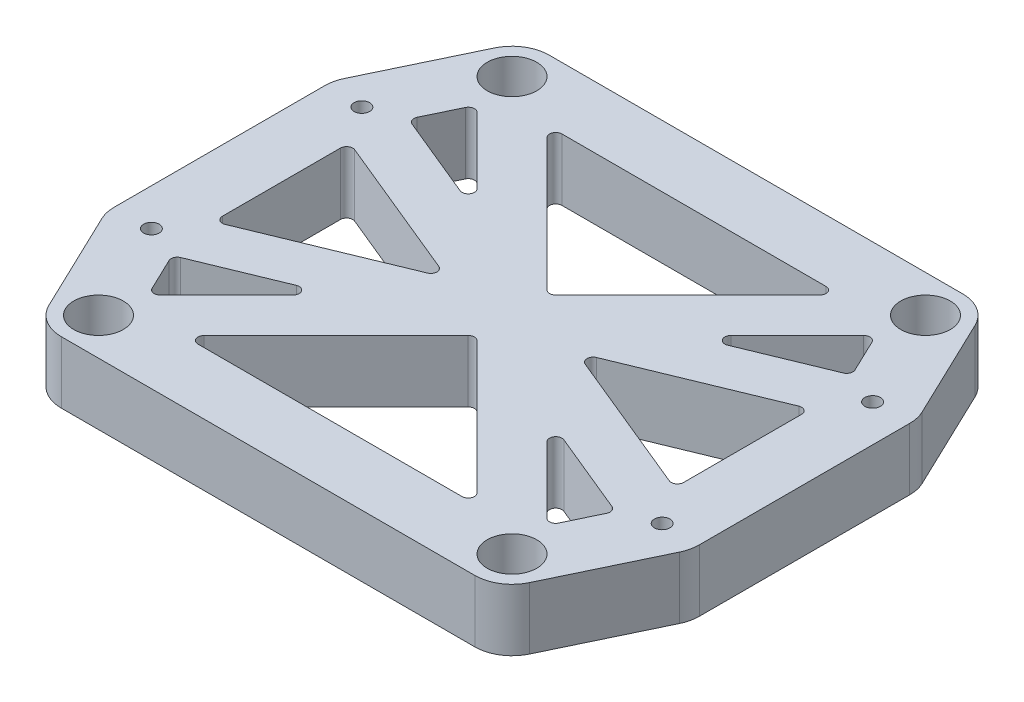
SolidWorks part; units mm, degrees
ref_plane "Front Plane" through (0, 0, 0) normal (0, 0, 1) x (1, 0, 0)
ref_plane "Top Plane" through (0, 0, 0) normal (0, 1, 0) x (1, 0, 0)
ref_plane "Right Plane" through (0, 0, 0) normal (1, 0, 0) x (0, 0, -1)
sketch "Sketch1" plane through (0, 0, 0) normal (0, 1, 0) x (1, 0, 0)
  line L1 (-52.3875, -21.59) -> (52.3875, -21.59) construction
  line L2 (-52.3875, -21.59) -> (-52.3875, 21.59) construction
  line L3 (-52.3875, 21.59) -> (52.3875, 21.59) construction
  line L4 (52.3875, -21.59) -> (52.3875, 21.59) construction
  line L5 (-52.3875, -21.59) -> (52.3875, 21.59) construction
  line L6 (-52.3875, 21.59) -> (52.3875, -21.59) construction
  line L7 (-42.418, -42.418) -> (42.418, -42.418) construction
  line L8 (-42.418, -42.418) -> (-42.418, 42.418) construction
  line L9 (-42.418, 42.418) -> (42.418, 42.418) construction
  line L10 (42.418, -42.418) -> (42.418, 42.418) construction
  line L11 (-42.418, -42.418) -> (42.418, 42.418) construction
  line L12 (-42.418, 42.418) -> (42.418, -42.418) construction
  line L13 (-65.0875, -55.118) -> (65.0875, -55.118)
  line L14 (-65.0875, -55.118) -> (-65.0875, 55.118)
  line L15 (-65.0875, 55.118) -> (65.0875, 55.118)
  line L16 (65.0875, -55.118) -> (65.0875, 55.118)
  line L17 (-65.0875, -55.118) -> (65.0875, 55.118) construction
  line L18 (-65.0875, 55.118) -> (65.0875, -55.118) construction
  circle A0 centre (-52.3875, 21.59) radius 1.5875
  circle A1 centre (52.3875, 21.59) radius 1.5875
  circle A2 centre (52.3875, -21.59) radius 1.5875
  circle A3 centre (-52.3875, -21.59) radius 1.5875
  circle A4 centre (-42.418, 42.418) radius 5.08
  circle A5 centre (42.418, 42.418) radius 5.08
  circle A6 centre (42.418, -42.418) radius 5.08
  circle A7 centre (-42.418, -42.418) radius 5.08
  point P0 (0, 0)
  point P10 (0, 0)
  point P19 (0, 0)
  dimension "D1" = 3.175
  dimension "D4" = 10.16
  dimension "D2" = 104.775
  dimension "D3" = 43.18
  dimension "D5" = 84.836
  dimension "D6" = 12.7
  dimension "D7" = 12.7
extrude "Boss-Extrude1" add sketch "Sketch1" along normal blind 12.7
sketch "Sketch2" plane through (0, 12.7, 0) normal (0, 1, 0) x (1, 0, 0)
  line L0 (-65.0875, 0) -> (65.0875, 0) construction
  line L1 (-65.0875, 55.118) -> (-65.0875, -55.118) construction
  line L2 (65.0875, -55.118) -> (65.0875, 55.118) construction
  line L3 (0, -55.118) -> (0, 55.118) construction
  line L4 (-65.0875, -55.118) -> (65.0875, -55.118) construction
  line L5 (65.0875, 55.118) -> (-65.0875, 55.118) construction
  line L6 (-42.418, 42.418) -> (-52.3875, 21.59) construction
  line L7 (-52.3875, 21.59) -> (-52.3875, -21.59) construction
  line L8 (-52.3875, -21.59) -> (-42.418, -42.418) construction
  line L9 (-42.418, -42.418) -> (42.418, -42.418) construction
  line L10 (42.418, -42.418) -> (52.3875, -21.59) construction
  line L11 (52.3875, -21.59) -> (52.3875, 21.59) construction
  line L12 (52.3875, 21.59) -> (42.418, 42.418) construction
  line L13 (42.418, 42.418) -> (-42.418, 42.418) construction
  line L14 (-42.418, 42.418) -> (0, 0) construction
  line L15 (0, 0) -> (-42.418, -42.418) construction
  line L16 (-52.3875, -21.59) -> (0, 0) construction
  line L17 (-52.3875, 21.59) -> (0, 0) construction
  line L18 (0, 0) -> (42.418, 42.418) construction
  line L19 (0, 0) -> (52.3875, 21.59) construction
  line L20 (0, 0) -> (52.3875, -21.59) construction
  line L21 (0, 0) -> (42.418, -42.418) construction
  line L22 (-27.0877, -37.338) -> (27.0877, -37.338)
  line L23 (0.898, -8.0822) -> (27.9858, -35.17)
  line L24 (-0.898, -8.0822) -> (-27.9858, -35.17)
  line L25 (-44.2456, -23.729) -> (-27.4425, -16.8041)
  line L26 (-26.0605, -18.8763) -> (-39.6659, -32.4817)
  line L27 (-44.9072, -25.4515) -> (-41.7095, -32.132)
  line L28 (-45.5536, -13.2791) -> (-16.1814, -1.1742)
  line L29 (-45.5536, 13.2791) -> (-16.1814, 1.1742)
  line L30 (-47.3075, 12.1049) -> (-47.3075, -12.1049)
  line L31 (-44.2456, 23.729) -> (-27.4425, 16.8041)
  line L32 (-39.6659, 32.4817) -> (-26.0605, 18.8763)
  line L33 (-41.7095, 32.132) -> (-44.9072, 25.4515)
  line L34 (0.898, 8.0822) -> (27.9858, 35.17)
  line L35 (27.0877, 37.338) -> (-27.0877, 37.338)
  line L36 (-27.9858, 35.17) -> (-0.898, 8.0822)
  line L37 (27.4425, 16.8041) -> (44.2456, 23.729)
  line L38 (44.9072, 25.4515) -> (41.7095, 32.132)
  line L39 (26.0605, 18.8763) -> (39.6659, 32.4817)
  line L40 (16.1814, 1.1742) -> (45.5536, 13.2791)
  line L41 (47.3075, -12.1049) -> (47.3075, 12.1049)
  line L42 (16.1814, -1.1742) -> (45.5536, -13.2791)
  line L43 (26.0605, -18.8763) -> (39.6659, -32.4817)
  line L44 (41.7095, -32.132) -> (44.9072, -25.4515)
  line L45 (27.4425, -16.8041) -> (44.2456, -23.729)
  line L46 (40.9348, -33.7506) -> (45.4868, -24.2406) construction
  line L47 (21.5669, -14.3827) -> (45.4868, -24.2406) construction
  line L48 (21.5669, -14.3827) -> (40.9348, -33.7506) construction
  line L49 (0, -7.1842) -> (30.1538, -37.338) construction
  line L50 (0, -7.1842) -> (-30.1538, -37.338) construction
  line L51 (-30.1538, -37.338) -> (30.1538, -37.338) construction
  line L52 (-45.4868, -24.2406) -> (-21.5669, -14.3827) construction
  line L53 (-45.4868, -24.2406) -> (-40.9348, -33.7506) construction
  line L54 (-21.5669, -14.3827) -> (-40.9348, -33.7506) construction
  line L55 (-47.3075, -14.0019) -> (-13.3322, 0) construction
  line L56 (-47.3075, 14.0019) -> (-13.3322, 0) construction
  line L57 (-47.3075, 14.0019) -> (-47.3075, -14.0019) construction
  line L58 (-45.4868, 24.2406) -> (-21.5669, 14.3827) construction
  line L59 (-40.9348, 33.7506) -> (-45.4868, 24.2406) construction
  line L60 (-40.9348, 33.7506) -> (-21.5669, 14.3827) construction
  line L61 (30.1538, 37.338) -> (-30.1538, 37.338) construction
  line L62 (-30.1538, 37.338) -> (0, 7.1842) construction
  line L63 (0, 7.1842) -> (30.1538, 37.338) construction
  line L64 (45.4868, 24.2406) -> (40.9348, 33.7506) construction
  line L65 (21.5669, 14.3827) -> (40.9348, 33.7506) construction
  line L66 (21.5669, 14.3827) -> (45.4868, 24.2406) construction
  line L67 (13.3322, 0) -> (47.3075, 14.0019) construction
  line L68 (47.3075, -14.0019) -> (47.3075, 14.0019) construction
  line L69 (13.3322, 0) -> (47.3075, -14.0019) construction
  line L70 (-35.5448, 39.1281) -> (-44.7675, 19.8603)
  line L71 (-44.7675, 19.8603) -> (-44.7675, -19.8603)
  line L72 (-44.7675, -19.8603) -> (-37.6174, -34.798)
  line L73 (-37.6174, -34.798) -> (37.6174, -34.798)
  line L74 (37.6174, -34.798) -> (44.7675, -19.8603)
  line L75 (44.7675, -19.8603) -> (44.7675, 19.8603)
  line L76 (44.7675, 19.8603) -> (35.5448, 39.1281)
  line L77 (42.418, 50.038) -> (-42.418, 50.038)
  line L78 (-49.2912, 45.7079) -> (-59.2607, 24.8799)
  line L79 (-60.0075, 21.59) -> (-60.0075, -21.59)
  line L80 (-59.2607, -24.8799) -> (-49.2912, -45.7079)
  line L81 (-42.418, -50.038) -> (42.418, -50.038)
  line L82 (49.2912, -45.7079) -> (59.2607, -24.8799)
  line L83 (60.0075, -21.59) -> (60.0075, 21.59)
  line L84 (59.2607, 24.8799) -> (49.2912, 45.7079)
  line L85 (47.2186, 50.038) -> (-47.2186, 50.038) construction
  line L86 (60.0075, 23.3197) -> (47.2186, 50.038) construction
  line L87 (60.0075, -23.3197) -> (60.0075, 23.3197) construction
  line L88 (47.2186, -50.038) -> (60.0075, -23.3197) construction
  line L89 (-47.2186, -50.038) -> (47.2186, -50.038) construction
  line L90 (-60.0075, -23.3197) -> (-47.2186, -50.038) construction
  line L91 (-60.0075, 23.3197) -> (-60.0075, -23.3197) construction
  line L92 (-47.2186, 50.038) -> (-60.0075, 23.3197) construction
  arc A0 (44.9072, -25.4515) -> (44.2456, -23.729) centre (43.7616, -24.9032) ccw
  arc A1 (39.6659, -32.4817) -> (41.7095, -32.132) centre (40.564, -31.5837) ccw
  arc A2 (26.0605, -18.8763) -> (27.4425, -16.8041) centre (26.9586, -17.9783) cw
  arc A3 (0.898, -8.0822) -> (-0.898, -8.0822) centre (0, -8.9803) ccw
  arc A4 (27.0877, -37.338) -> (27.9858, -35.17) centre (27.0877, -36.068) ccw
  arc A5 (-27.0877, -37.338) -> (-27.9858, -35.17) centre (-27.0877, -36.068) cw
  arc A6 (-44.2456, -23.729) -> (-44.9072, -25.4515) centre (-43.7616, -24.9032) ccw
  arc A7 (-39.6659, -32.4817) -> (-41.7095, -32.132) centre (-40.564, -31.5837) cw
  arc A8 (-27.4425, -16.8041) -> (-26.0605, -18.8763) centre (-26.9586, -17.9783) cw
  arc A9 (-16.1814, -1.1742) -> (-16.1814, 1.1742) centre (-16.6653, 0) ccw
  arc A10 (-45.5536, -13.2791) -> (-47.3075, -12.1049) centre (-46.0375, -12.1049) cw
  arc A11 (-45.5536, 13.2791) -> (-47.3075, 12.1049) centre (-46.0375, 12.1049) ccw
  arc A12 (-44.2456, 23.729) -> (-44.9072, 25.4515) centre (-43.7616, 24.9032) cw
  arc A13 (-39.6659, 32.4817) -> (-41.7095, 32.132) centre (-40.564, 31.5837) ccw
  arc A14 (-27.0877, 37.338) -> (-27.9858, 35.17) centre (-27.0877, 36.068) ccw
  arc A15 (27.9858, 35.17) -> (27.0877, 37.338) centre (27.0877, 36.068) ccw
  arc A16 (41.7095, 32.132) -> (39.6659, 32.4817) centre (40.564, 31.5837) ccw
  arc A17 (44.2456, 23.729) -> (44.9072, 25.4515) centre (43.7616, 24.9032) ccw
  arc A18 (45.5536, 13.2791) -> (47.3075, 12.1049) centre (46.0375, 12.1049) cw
  arc A19 (47.3075, -12.1049) -> (45.5536, -13.2791) centre (46.0375, -12.1049) cw
  arc A20 (16.1814, 1.1742) -> (16.1814, -1.1742) centre (16.6653, 0) ccw
  arc A21 (27.4425, 16.8041) -> (26.0605, 18.8763) centre (26.9586, 17.9783) cw
  arc A22 (0.898, 8.0822) -> (-0.898, 8.0822) centre (0, 8.9803) cw
  arc A23 (-27.4425, 16.8041) -> (-26.0605, 18.8763) centre (-26.9586, 17.9783) ccw
  arc A24 (42.418, 50.038) -> (49.2912, 45.7079) centre (42.418, 42.418) cw
  arc A25 (60.0075, 21.59) -> (59.2607, 24.8799) centre (52.3875, 21.59) ccw
  arc A26 (59.2607, -24.8799) -> (60.0075, -21.59) centre (52.3875, -21.59) ccw
  arc A27 (42.418, -50.038) -> (49.2912, -45.7079) centre (42.418, -42.418) ccw
  arc A28 (-49.2912, -45.7079) -> (-42.418, -50.038) centre (-42.418, -42.418) ccw
  arc A29 (-60.0075, -21.59) -> (-59.2607, -24.8799) centre (-52.3875, -21.59) ccw
  arc A30 (-59.2607, 24.8799) -> (-60.0075, 21.59) centre (-52.3875, 21.59) ccw
  arc A31 (-42.418, 50.038) -> (-49.2912, 45.7079) centre (-42.418, 42.418) ccw
  dimension "D9" = 1.27
  dimension "D12" = 7.62
  dimension "D1" = 5.08
  dimension "D2" = 5.08
  dimension "D3" = 5.08
  dimension "D4" = 5.08
  dimension "D5" = 5.08
  dimension "D6" = 5.08
  dimension "D7" = 5.08
  dimension "D8" = 5.08
  dimension "D10" = 7.62
  dimension "D11" = 7.62
extrude "Cut-Extrude1" cut sketch "Sketch2" against normal through all both and the other way through all flip side to cut
